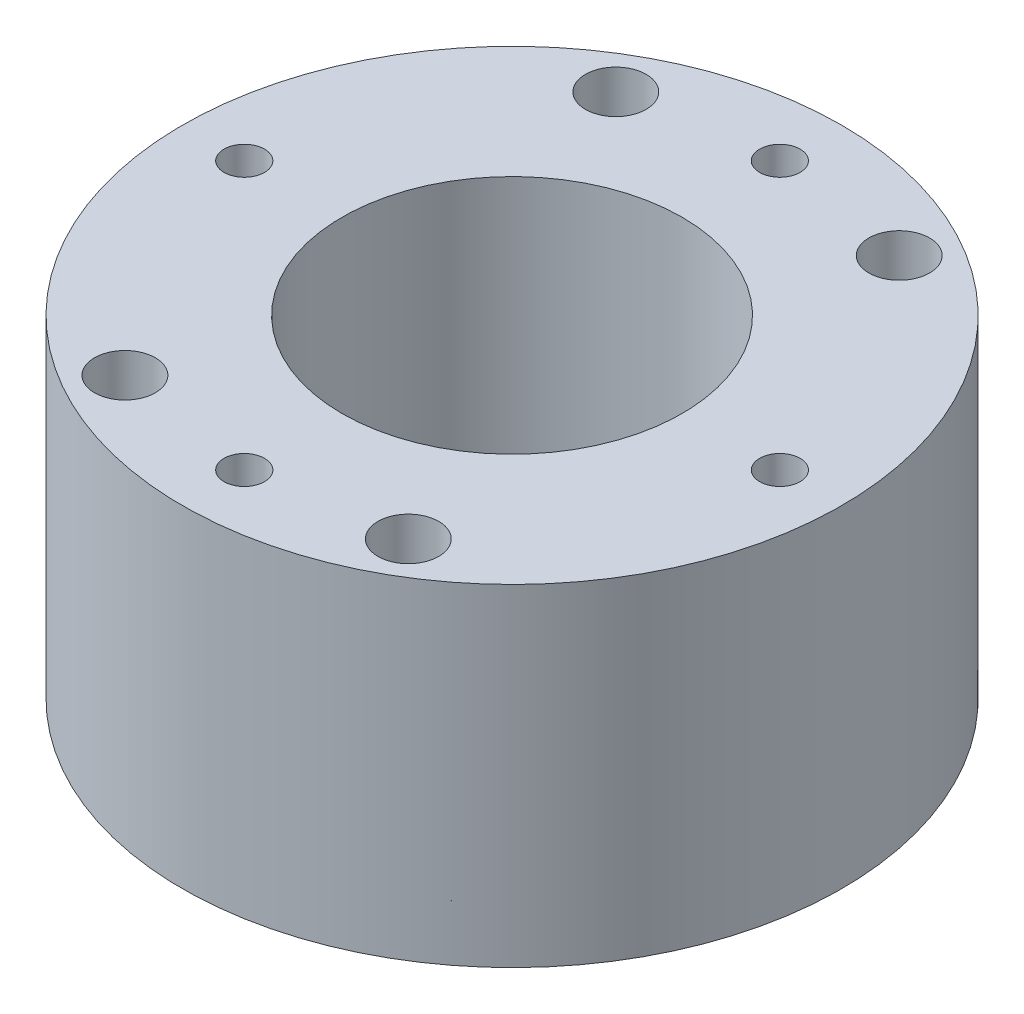
SolidWorks part; units mm, degrees
ref_plane "Front Plane" through (0, 0, 0) normal (0, 0, 1) x (1, 0, 0)
ref_plane "Top Plane" through (0, 0, 0) normal (0, 1, 0) x (1, 0, 0)
ref_plane "Right Plane" through (0, 0, 0) normal (1, 0, 0) x (0, 0, -1)
sketch "Sketch1" plane through (0, 0, 0) normal (0, 0, 1) x (1, 0, 0)
  line L0 (0, 0) -> (0, 26.7041) construction
  line L1 (14.2875, 27.8791) -> (27.69, 27.8791)
  line L2 (27.69, 27.8791) -> (27.69, 0)
  line L3 (27.69, 0) -> (14.2875, 0)
  line L4 (14.2875, 0) -> (14.2875, 27.8791)
  dimension "D1" = 27.69
  dimension "D2" = 27.8791
  dimension "D3" = 14.2875
revolve "Revolve1" add sketch "Sketch1" angle 360 about L0
sketch "Sketch2" plane through (0, 0, 0) normal (0, 1, 0) x (1, 0, 0)
  circle A0 centre (0, 0) radius 22.5 construction
  point P3 (0, 22.5)
  point P4 (22.5, 0)
  point P5 (-22.5, 0)
  point P6 (0, -22.5)
  dimension "D1" = 45
hole_wizard "CBORE for M3 SBHCS1" positions "Sketch2" profile "Sketch3" counterbore size "M3" standard "ANSI Metric" end condition up to next
sketch "Sketch3" plane through (0, 0, 22.5) normal (1, 0, 0) x (0, 0, -1)
  line L0 (0, 0) -> (0, 27.8791)
  line L1 (0, 27.8791) -> (1.7, 27.8791)
  line L3 (1.7, 27.8791) -> (1.7, 2.15)
  line L4 (1.7, 2.15) -> (3.35, 2.15)
  line L5 (3.35, 2.15) -> (3.35, 0)
  line L7 (3.35, 0) -> (0, 0)
  line L11 (0, -6.35) -> (0, 107.95) construction
  dimension "Thru Hole Dia." = 3.4
  dimension "Thru Hole Depth" = 27.8791
  dimension "C'Bore Dia." = 6.7
  dimension "C'Bore Depth" = 2.15
sketch "Sketch4" plane through (0, 0, 0) normal (0, 1, 0) x (1, 0, 0)
  circle A0 centre (0, 0) radius 23.8125 construction
  point P2 (-11.9063, 20.6222)
  point P7 (11.9062, 20.6222)
  point P8 (23.8125, 0)
  point P9 (11.9063, -20.6222)
  point P10 (-11.9062, -20.6222)
  point P11 (-23.8125, 0)
  point P12 (0, 0)
  dimension "D1" = 47.625
  dimension "D2" = 6
hole_wizard "#10 Clearance Hole1" positions "Sketch4" profile "Sketch6" hole size "#10" standard "ANSI Inch"
sketch "Sketch6" plane through (-11.9062, 0, 20.6222) normal (1, 0, 0) x (0, 0, -1)
  line L0 (0, 0) -> (0, 27.8791)
  line L1 (0, 27.8791) -> (2.5527, 27.8791)
  line L2 (2.5527, 27.8791) -> (2.5527, 0)
  line L5 (2.5527, 0) -> (0, 0)
  line L11 (0, -6.35) -> (0, 107.95) construction
  dimension "Thru Hole Dia." = 5.1054
  dimension "Thru Hole Depth" = 27.8791
